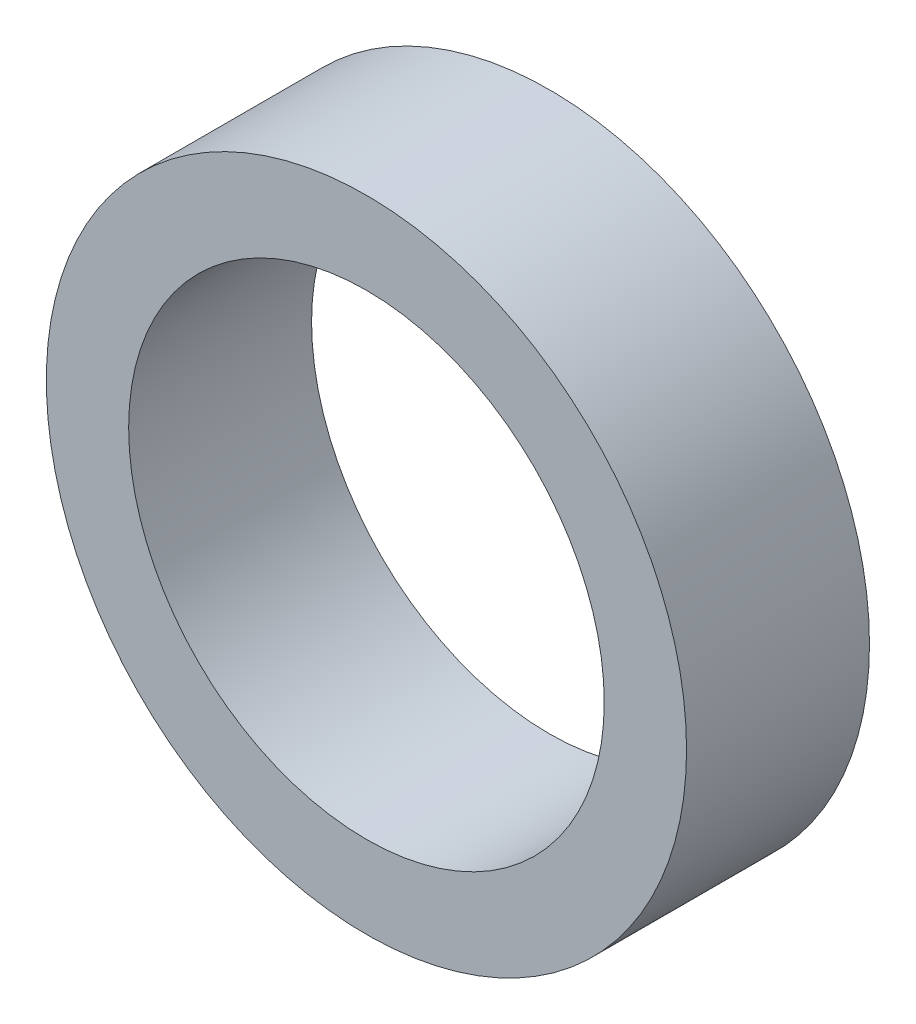
SolidWorks part; units mm, degrees
material "PETG"
ref_plane "Front Plane" through (0, 0, 0) normal (0, 0, 1) x (1, 0, 0)
ref_plane "Top Plane" through (0, 0, 0) normal (0, 1, 0) x (1, 0, 0)
ref_plane "Right Plane" through (0, 0, 0) normal (1, 0, 0) x (0, 0, -1)
sketch "Эскиз1" plane through (0, 0, 0) normal (0, 0, 1) x (1, 0, 0)
  circle A2 centre (0, 0) radius 2.6
  circle A3 centre (0, 0) radius 3.5
  dimension "D1" = 7
  dimension "D3" = 5.2
extrude "Бобышка-Вытянуть1" add sketch "Эскиз1" along normal mid plane 2
